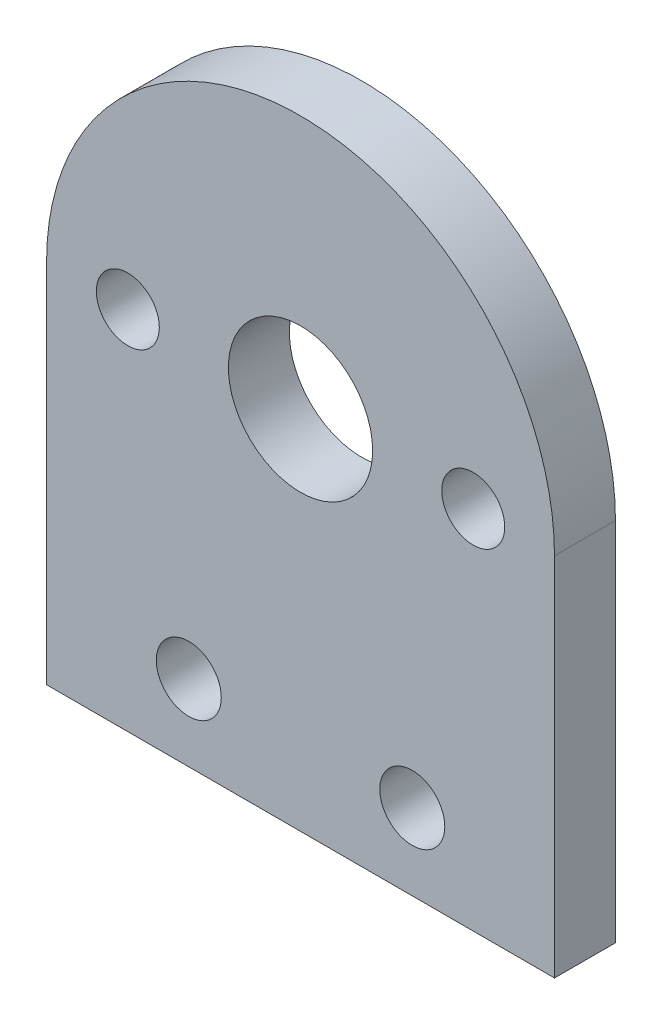
SolidWorks part; units mm, degrees
ref_plane "Front" through (0, 0, 0) normal (0, 0, 1) x (1, 0, 0)
ref_plane "Top" through (0, 0, 0) normal (0, 1, 0) x (1, 0, 0)
ref_plane "Right" through (0, 0, 0) normal (1, 0, 0) x (0, 0, -1)
sketch "草图1" plane through (0, 0, 0) normal (0, 0, 1) x (1, 0, 0)
  line L0 (-25, 0) -> (0, 0)
  line L1 (0, 0) -> (0, 18)
  line L2 (-25, 18) -> (-25, 0)
  arc A0 (0, 18) -> (-25, 18) centre (-12.5, 18) ccw
  dimension "D2" = 18
  dimension "D1" = 25
extrude "凸台-拉伸1" add sketch "草图1" along normal mid plane 3
sketch "草图2" plane through (0, 0, 1.5) normal (0, 0, 1) x (1, 0, 0)
  line L0 (-7, 3.75) -> (-18, 3.75) construction
  line L1 (-25, 0) -> (0, 0) construction
  circle A0 centre (-18, 3.75) radius 1.6
  circle A1 centre (-7, 3.75) radius 1.6
  arc A2 (0, 18) -> (-25, 18) centre (-12.5, 18) ccw construction
  point P6 (-12.5, 3.75)
  point P10 (-12.5, 30.5)
  dimension "D1" = 3.2
  dimension "D2" = 3.75
  dimension "D3" = 11
  dimension "D4" = 0
extrude "切除-拉伸1" cut sketch "草图2" against normal blind 3
sketch "草图3" plane through (0, 0, 1.5) normal (0, 0, 1) x (1, 0, 0)
  circle A0 centre (-12.5, 18) radius 8.5 construction
  circle A1 centre (-4, 18) radius 1.55
  circle A2 centre (-21, 18) radius 1.55
  circle A3 centre (-12.5, 18) radius 3.55
  dimension "D1" = 17
  dimension "D2" = 3.1
  dimension "D3" = 3.1
  dimension "D4" = 7.1
extrude "切除-拉伸2" cut sketch "草图3" against normal blind 3 contours A3 | A2 | A1
